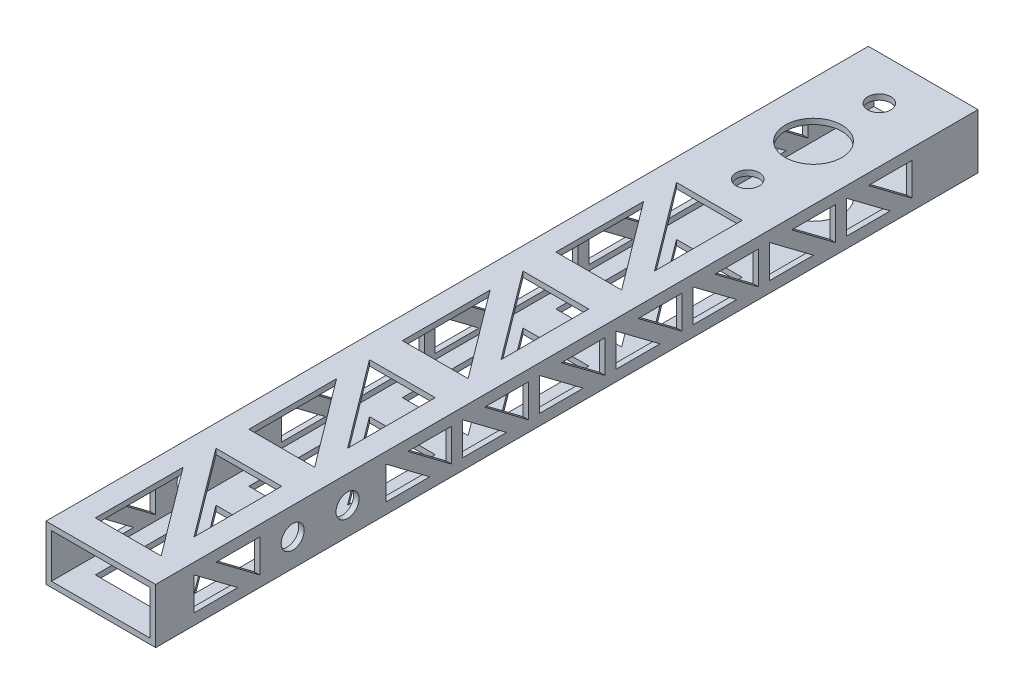
SolidWorks part; units mm, degrees
ref_plane "前视基准面" through (0, 0, 0) normal (0, 0, 1) x (1, 0, 0)
ref_plane "上视基准面" through (0, 0, 0) normal (0, 1, 0) x (1, 0, 0)
ref_plane "右视基准面" through (0, 0, 0) normal (1, 0, 0) x (0, 0, -1)
other "Configuration Table"
sketch "草图1" plane through (0, 0, 0) normal (0, 0, 1) x (1, 0, 0)
  line L1 (0, 0) -> (20, 0)
  line L2 (0, 0) -> (0, -10)
  line L3 (0, -10) -> (20, -10)
  line L4 (20, 0) -> (20, -10)
  dimension "D1" = 20
  dimension "D2" = 10
extrude "拉伸-薄壁1" add sketch "草图1" along normal blind 150 thin
sketch "草图2" plane through (20, 0, 0) normal (1, 0, 0) x (0, 0, -1)
  line L0 (-150, -10) -> (-150, 0) construction
  line L1 (-108, -2) -> (-108, -8)
  line L2 (-108, -8) -> (-100, -8)
  line L3 (-75, 0) -> (-75, -10) construction
  line L4 (-150, 0) -> (0, 0) construction
  line L5 (-150, -10) -> (0, -10) construction
  line L6 (-125, -5) -> (-115, -5) construction
  line L7 (-150, -5) -> (-125, -5) construction
  line L8 (-100, -8) -> (-108, -2)
  line L9 (-104, -2) -> (-96, -2)
  line L10 (-96, -2) -> (-96, -8)
  line L11 (-96, -8) -> (-104, -2)
  line L12 (-90, -2) -> (-82, -2)
  line L13 (-82, -2) -> (-82, -8)
  line L14 (-82, -8) -> (-90, -2)
  line L15 (-86, -8) -> (-94, -2)
  line L16 (-94, -8) -> (-86, -8)
  line L17 (-94, -2) -> (-94, -8)
  line L18 (-76, -2) -> (-68, -2)
  line L19 (-68, -2) -> (-68, -8)
  line L20 (-68, -8) -> (-76, -2)
  line L21 (-72, -8) -> (-80, -2)
  line L22 (-80, -8) -> (-72, -8)
  line L23 (-80, -2) -> (-80, -8)
  line L24 (-62, -2) -> (-54, -2)
  line L25 (-54, -2) -> (-54, -8)
  line L26 (-54, -8) -> (-62, -2)
  line L27 (-58, -8) -> (-66, -2)
  line L28 (-66, -8) -> (-58, -8)
  line L29 (-66, -2) -> (-66, -8)
  line L30 (-48, -2) -> (-40, -2)
  line L31 (-40, -2) -> (-40, -8)
  line L32 (-40, -8) -> (-48, -2)
  line L33 (-44, -8) -> (-52, -2)
  line L34 (-52, -8) -> (-44, -8)
  line L35 (-52, -2) -> (-52, -8)
  line L36 (-34, -2) -> (-26, -2)
  line L37 (-26, -2) -> (-26, -8)
  line L38 (-26, -8) -> (-34, -2)
  line L39 (-30, -8) -> (-38, -2)
  line L40 (-38, -8) -> (-30, -8)
  line L41 (-38, -2) -> (-38, -8)
  line L42 (-20, -2) -> (-12, -2)
  line L43 (-12, -2) -> (-12, -8)
  line L44 (-12, -8) -> (-20, -2)
  line L45 (-16, -8) -> (-24, -2)
  line L46 (-24, -8) -> (-16, -8)
  line L47 (-24, -2) -> (-24, -8)
  line L48 (-139, -2) -> (-131, -2)
  line L49 (-131, -2) -> (-131, -8)
  line L50 (-131, -8) -> (-139, -2)
  line L51 (-135, -8) -> (-143, -2)
  line L52 (-143, -8) -> (-135, -8)
  line L53 (-143, -2) -> (-143, -8)
  circle A2 centre (-115, -5) radius 2.1
  circle A3 centre (-125, -5) radius 2.1
  dimension "D1" = 25
  dimension "D2" = 10
  dimension "D3" = 4.2
  dimension "D4" = 6
  dimension "D5" = 8
  dimension "D6" = 7
  dimension "D7" = 6
  dimension "D8" = 8
  dimension "D9" = 12
  dimension "D11" = 14
  dimension "D13" = 35
  dimension "D10" = 7
  dimension "D12" = 2
extrude "切除-拉伸1" cut sketch "草图2" against normal through all
sketch "草图3" plane through (0, 0, 0) normal (0, 1, 0) x (1, 0, 0)
  line L0 (0, -20) -> (20, -20) construction
  line L1 (0, -150) -> (0, 0) construction
  line L2 (20, -150) -> (20, 0) construction
  line L3 (10, 0) -> (10, -20) construction
  line L4 (20, 0) -> (0, 0) construction
  line L5 (4, -129) -> (4, -145)
  line L6 (4, -145) -> (16, -145)
  line L7 (16, -145) -> (4, -129)
  line L8 (4, -123) -> (16, -123)
  line L9 (16, -123) -> (16, -139)
  line L10 (16, -139) -> (4, -123)
  line L12 (10, -150) -> (10, 0) construction
  line L13 (20, -150) -> (0, -150) construction
  line L14 (4, -95) -> (16, -95)
  line L15 (16, -95) -> (16, -111)
  line L16 (16, -111) -> (4, -95)
  line L17 (16, -117) -> (4, -101)
  line L18 (4, -101) -> (4, -117)
  line L19 (4, -117) -> (16, -117)
  line L20 (4, -67) -> (16, -67)
  line L21 (16, -67) -> (16, -83)
  line L22 (16, -83) -> (4, -67)
  line L23 (16, -89) -> (4, -73)
  line L24 (4, -73) -> (4, -89)
  line L25 (4, -89) -> (16, -89)
  line L26 (4, -39) -> (16, -39)
  line L27 (16, -39) -> (16, -55)
  line L28 (16, -55) -> (4, -39)
  line L29 (16, -61) -> (4, -45)
  line L30 (4, -45) -> (4, -61)
  line L31 (4, -61) -> (16, -61)
  circle A0 centre (10, -20) radius 5.15
  circle A1 centre (10, -8) radius 2.1
  circle A2 centre (10, -32) radius 2.1
  dimension "D1" = 10.3
  dimension "D3" = 4.2
  dimension "D2" = 20
  dimension "D4" = 12
  dimension "D5" = 12
  dimension "D6" = 16
  dimension "D7" = 12
  dimension "D8" = 16
  dimension "D9" = 22
  dimension "D10" = 28
  dimension "5" = 5
  dimension "D11" = 4
extrude "切除-拉伸2" cut sketch "草图3" against normal through all
